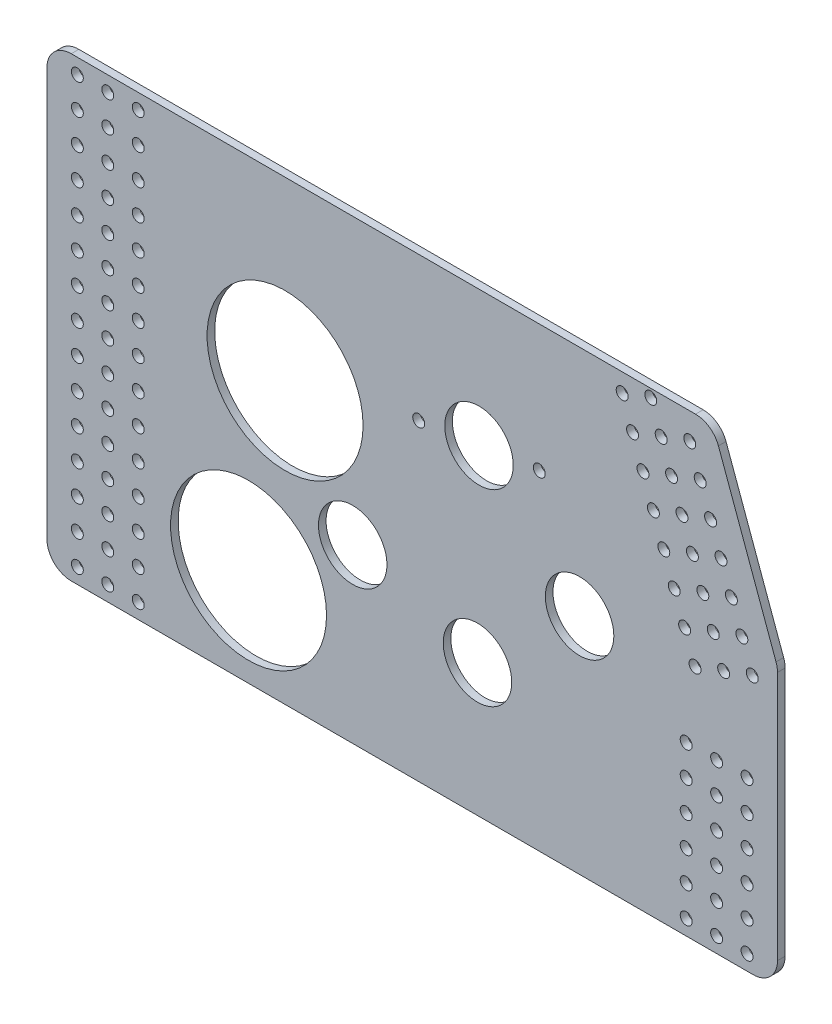
SolidWorks part; units mm, degrees
ref_plane "Front Plane" through (0, 0, 0) normal (0, 0, 1) x (1, 0, 0)
ref_plane "Top Plane" through (0, 0, 0) normal (0, 1, 0) x (1, 0, 0)
ref_plane "Right Plane" through (0, 0, 0) normal (1, 0, 0) x (0, 0, -1)
sketch "Sketch1" plane through (0, 0, 0) normal (0, 0, 1) x (1, 0, 0)
  line B0 (-152.4, 0) -> (152.4, 0)
  line B1 (152.4, 0) -> (152.4, 116.0843)
  line B2 (152.4, 116.0843) -> (125.3149, 190.5)
  line B3 (125.3149, 190.5) -> (-152.4, 190.5)
  line B4 (-152.4, 190.5) -> (-152.4, 0)
  circle B5 centre (-139.7, 184.15) radius 2.4892
  circle B6 centre (-127, 184.15) radius 2.4892
  circle B7 centre (-114.3, 184.15) radius 2.4892
  circle B8 centre (-127, 171.45) radius 2.4892
  circle B9 centre (-114.3, 171.45) radius 2.4892
  circle B10 centre (-127, 158.75) radius 2.4892
  circle B11 centre (-114.3, 158.75) radius 2.4892
  circle B12 centre (-127, 146.05) radius 2.4892
  circle B13 centre (-114.3, 146.05) radius 2.4892
  circle B14 centre (-127, 133.35) radius 2.4892
  circle B15 centre (-114.3, 133.35) radius 2.4892
  circle B16 centre (-127, 120.65) radius 2.4892
  circle B17 centre (-114.3, 120.65) radius 2.4892
  circle B18 centre (-127, 107.95) radius 2.4892
  circle B19 centre (-114.3, 107.95) radius 2.4892
  circle B20 centre (-127, 95.25) radius 2.4892
  circle B21 centre (-114.3, 95.25) radius 2.4892
  circle B22 centre (-127, 82.55) radius 2.4892
  circle B23 centre (-114.3, 82.55) radius 2.4892
  circle B24 centre (-127, 69.85) radius 2.4892
  circle B25 centre (-114.3, 69.85) radius 2.4892
  circle B26 centre (-127, 57.15) radius 2.4892
  circle B27 centre (-114.3, 57.15) radius 2.4892
  circle B28 centre (-127, 44.45) radius 2.4892
  circle B29 centre (-114.3, 44.45) radius 2.4892
  circle B30 centre (-127, 31.75) radius 2.4892
  circle B31 centre (-114.3, 31.75) radius 2.4892
  circle B32 centre (-127, 19.05) radius 2.4892
  circle B33 centre (-114.3, 19.05) radius 2.4892
  circle B34 centre (-127, 6.35) radius 2.4892
  circle B35 centre (-114.3, 6.35) radius 2.4892
  circle B36 centre (-139.7, 171.45) radius 2.4892
  circle B37 centre (-139.7, 158.75) radius 2.4892
  circle B38 centre (-139.7, 146.05) radius 2.4892
  circle B39 centre (-139.7, 133.35) radius 2.4892
  circle B40 centre (-139.7, 120.65) radius 2.4892
  circle B41 centre (-139.7, 107.95) radius 2.4892
  circle B42 centre (-139.7, 95.25) radius 2.4892
  circle B43 centre (-139.7, 82.55) radius 2.4892
  circle B44 centre (-139.7, 69.85) radius 2.4892
  circle B45 centre (-139.7, 57.15) radius 2.4892
  circle B46 centre (-139.7, 44.45) radius 2.4892
  circle B47 centre (-139.7, 31.75) radius 2.4892
  circle B48 centre (-139.7, 19.05) radius 2.4892
  circle B49 centre (-139.7, 6.35) radius 2.4892
  circle B50 centre (87.5907, 182.7494) radius 2.4892
  circle B51 centre (99.5248, 187.093) radius 2.4892
  circle B52 centre (115.8026, 179.5026) radius 2.4892
  circle B53 centre (91.9344, 170.8153) radius 2.4892
  circle B54 centre (103.8685, 175.1589) radius 2.4892
  circle B55 centre (120.1462, 167.5685) radius 2.4892
  circle B56 centre (96.278, 158.8812) radius 2.4892
  circle B57 centre (108.2121, 163.2248) radius 2.4892
  circle B58 centre (124.4899, 155.6344) radius 2.4892
  circle B59 centre (100.6217, 146.9471) radius 2.4892
  circle B60 centre (112.5558, 151.2907) radius 2.4892
  circle B61 centre (128.8335, 143.7003) radius 2.4892
  circle B62 centre (104.9653, 135.013) radius 2.4892
  circle B63 centre (116.8994, 139.3566) radius 2.4892
  circle B64 centre (133.1772, 131.7662) radius 2.4892
  circle B65 centre (109.309, 123.0789) radius 2.4892
  circle B66 centre (121.2431, 127.4226) radius 2.4892
  circle B67 centre (137.5208, 119.8321) radius 2.4892
  circle B68 centre (113.6526, 111.1448) radius 2.4892
  circle B69 centre (125.5867, 115.4885) radius 2.4892
  circle B70 centre (141.8645, 107.898) radius 2.4892
  circle B71 centre (117.9963, 99.2107) radius 2.4892
  circle B72 centre (129.9304, 103.5544) radius 2.4892
  circle B73 centre (146.2081, 95.9639) radius 2.4892
  circle B74 centre (114.3, 69.85) radius 2.4892
  circle B75 centre (127, 69.85) radius 2.4892
  circle B76 centre (139.7, 69.85) radius 2.4892
  circle B77 centre (114.3, 57.15) radius 2.4892
  circle B78 centre (127, 57.15) radius 2.4892
  circle B79 centre (139.7, 57.15) radius 2.4892
  circle B80 centre (114.3, 44.45) radius 2.4892
  circle B81 centre (127, 44.45) radius 2.4892
  circle B82 centre (139.7, 44.45) radius 2.4892
  circle B83 centre (114.3, 31.75) radius 2.4892
  circle B84 centre (127, 31.75) radius 2.4892
  circle B85 centre (139.7, 31.75) radius 2.4892
  circle B86 centre (114.3, 19.05) radius 2.4892
  circle B87 centre (127, 19.05) radius 2.4892
  circle B88 centre (139.7, 19.05) radius 2.4892
  circle B89 centre (114.3, 6.35) radius 2.4892
  circle B90 centre (127, 6.35) radius 2.4892
  circle B91 centre (139.7, 6.35) radius 2.4892
  circle B92 centre (11.8508, 132.0168) radius 14.2875
  circle B93 centre (-24.8197, 71.7449) radius 14.2875
  circle B94 centre (57.6351, 95.7125) radius 14.2875
  circle B95 centre (23.7546, 49.6787) radius 14.2875
  circle B96 centre (-65.2702, 36.9534) radius 29.9974
  circle B97 centre (-65.2702, 106.5494) radius 29.9974
  circle B98 centre (-7.8935, 147.9957) radius 2.4892
  circle B99 centre (31.595, 116.038) radius 2.4892
  circle B100 centre (5.6698, 80.2095) radius 2.4892
  circle B101 centre (41.8394, 80.2095) radius 2.4892
  circle B102 centre (41.8394, 19.1479) radius 2.4892
  circle B103 centre (5.6698, 19.1479) radius 2.4892
sketch_block_instance "Block-OuterPlate-1"
sketch_block "Block-OuterPlate" parameters "D1"=4.9784, "D7"=4.9784, "D8"=4.9784, "D9"=4.9784, "D11"=4.9784, "D12"=4.9784, "D13"=4.9784, "D15"=59.9948, "D16"=59.9948, "D17"=28.575, "D18"=28.575, "D19"=28.575, "D20"=28.575, "D21"=4.9784, "D22"=4.9784, "D23"=4.9784, "D24"=4.9784, "D25"=4.9784, "D26"=4.9784, "D2"=6.35, "D3"=12.7, "D4"=12.7, "D5"=12.7, "D6"=6.35, "D10"=12.7, "D14"=12.7, "D27"=36.1696, "D28"=18.0848, "D29"=30.5308, "D30"=30.5308
extrude "Boss-Extrude1" add sketch "Sketch1" along normal blind 3.175
sketch "Sketch2" plane through (0, 0, 3.175) normal (0, 0, 1) x (1, 0, 0)
  circle A0 centre (146.2081, 95.9639) radius 2.4892
  dimension "D1" = 4.9784
extrude "Boss-Extrude2" add sketch "Sketch2" against normal blind 3.175
fillet "Fillet1" radius 10.16 5 edges at (-152.4, 0, 1.5875) (152.4, 0, 1.5875) (152.4, 116.0843, 1.5875) (125.3149, 190.5, 1.5875) (-152.4, 190.5, 1.5875)
sketch "Sketch7" plane through (0, 0, 3.175) normal (0, 0, 1) x (1, 0, 0)
  circle A0 centre (11.8508, 132.0168) radius 14.2875 construction
  circle A1 centre (57.6351, 95.7125) radius 14.2875 construction
  circle A2 centre (23.7546, 49.6787) radius 14.2875 construction
  circle A3 centre (11.8508, 132.0168) radius 14.2875
  circle A4 centre (57.6351, 95.7125) radius 14.2875
  circle A5 centre (23.7546, 49.6787) radius 14.2875
  circle A6 centre (41.8394, 19.1479) radius 2.4892 construction
  circle A7 centre (5.6698, 19.1479) radius 2.4892 construction
  circle A8 centre (-7.8935, 147.9957) radius 2.4892 construction
  circle A9 centre (31.595, 116.038) radius 2.4892 construction
  circle A10 centre (41.8394, 80.2095) radius 2.4892 construction
  circle A11 centre (5.6698, 80.2095) radius 2.4892 construction
  circle A12 centre (41.8394, 19.1479) radius 2.4892
  circle A13 centre (5.6698, 19.1479) radius 2.4892
  circle A14 centre (-7.8935, 147.9957) radius 2.4892
  circle A15 centre (31.595, 116.038) radius 2.4892
  circle A16 centre (41.8394, 80.2095) radius 2.4892
  circle A17 centre (5.6698, 80.2095) radius 2.4892
extrude "Boss-Extrude4" add sketch "Sketch7" against normal up to surface (3.175 mm away) up to face at (25.4598, 99.6963, 0)
sketch "Sketch8" plane through (0, 0, 3.175) normal (0, 0, 1) x (1, 0, 0)
  line L0 (2.7114, 130.4399) -> (53.017, 137.5099) construction
  line L1 (27.8642, 133.9749) -> (2.7114, 133.9749) construction
  line L2 (2.7114, 130.4399) -> (2.7114, 133.9749) construction
  circle A0 centre (-24.8197, 71.7449) radius 14.2875 construction
  circle A1 centre (-24.8197, 71.7449) radius 14.2875
  circle A2 centre (-24.8197, 71.7449) radius 13.97
  circle A3 centre (27.2348, 55.2349) radius 40.64
  circle A4 centre (27.2348, 55.2349) radius 14.2875
  circle A5 centre (27.2348, 55.2349) radius 22.86
  circle A6 centre (69.8319, 93.3349) radius 34.29
  circle A7 centre (69.8319, 93.3349) radius 14.2875
  circle A8 centre (69.8319, 93.3349) radius 12.7
  circle A9 centre (27.8642, 133.9749) radius 45.72
  circle A10 centre (27.8642, 133.9749) radius 14.2875
  circle A11 centre (53.017, 137.5099) radius 2.4892
  circle A12 centre (2.7114, 130.4399) radius 2.4892
  dimension "D1" = 27.94
  dimension "D2" = 81.28
  dimension "D3" = 28.575
  dimension "D4" = 45.72
  dimension "D5" = 68.58
  dimension "D6" = 28.575
  dimension "D7" = 25.4
  dimension "D8" = 91.44
  dimension "D12" = 28.575
  dimension "D13" = 50.8
  dimension "D14" = 4.9784
  dimension "D9" = 16.51
  dimension "D10" = 38.1
  dimension "D11" = 40.64
  dimension "D15" = 8
extrude "Cut-Extrude1" cut sketch "Sketch8" against normal through all contours A4 | A8 | A9 A7 A8 | A10 | A7 A9 | A12 | A11
sketch "Sketch11" plane through (0, 0, 3.175) normal (0, 0, 1) x (1, 0, 0)
  circle A0 centre (-65.2702, 36.9534) radius 29.9974 construction
  circle A1 centre (-65.2702, 106.5494) radius 29.9974 construction
  circle A2 centre (-65.2702, 36.9534) radius 29.9974
  circle A3 centre (-65.2702, 106.5494) radius 29.9974
extrude "Boss-Extrude5" add sketch "Sketch11" against normal up to surface (3.175 mm away) up to face at (41.5223, 55.2349, 0)
sketch "Sketch10" plane through (0, 0, 3.175) normal (0, 0, 1) x (1, 0, 0)
  circle A0 centre (-24.8197, 71.7449) radius 14.2875 construction
  circle A1 centre (-24.8197, 71.7449) radius 14.2875
  circle A2 centre (-24.8197, 71.7449) radius 45.72
  circle A3 centre (-53.0343, 117.0118) radius 7.62
  circle A5 centre (-68.2743, 40.8118) radius 7.62
  circle A6 centre (-53.0343, 117.0118) radius 32.5374
  circle A8 centre (-68.2743, 40.8118) radius 32.5374
  dimension "D1" = 91.44
  dimension "D2" = 15.24
  dimension "D5" = 65.0748
  dimension "D6" = 65.0748
  dimension "D3" = 76.2
  dimension "D4" = 15.24
extrude "Cut-Extrude2" cut sketch "Sketch10" against normal through all contours A2 A8 A5 | A2 A8 | A2 A6 A3 | A2 A6 | A3 | A5
